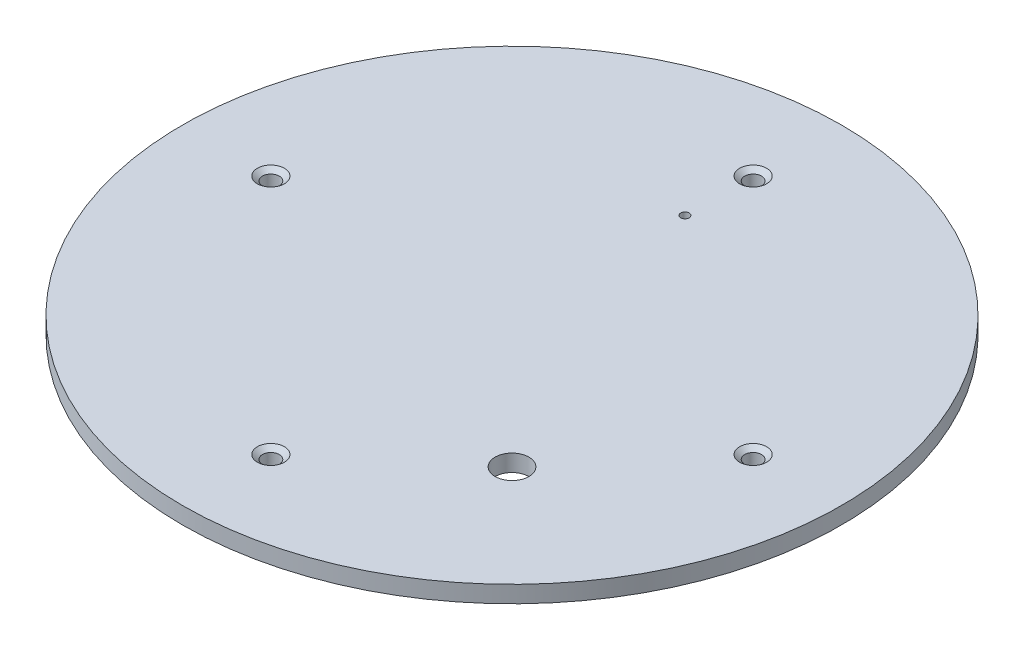
SolidWorks part; units mm, degrees
material "1060 Alloy"
ref_plane "Front Plane" through (0, 0, 0) normal (0, 0, 1) x (1, 0, 0)
ref_plane "Top Plane" through (0, 0, 0) normal (0, 1, 0) x (1, 0, 0)
ref_plane "Right Plane" through (0, 0, 0) normal (1, 0, 0) x (0, 0, -1)
sketch "Sketch1" plane through (0, 0, 0) normal (0, 1, 0) x (1, 0, 0)
  circle A0 centre (0, 0) radius 19.53
  dimension "D1" = 39.06
extrude "Boss-Extrude1" add sketch "Sketch1" along normal blind 1
sketch "Sketch6" plane through (0, 1, 0) normal (0, 1, 0) x (1, 0, 0)
  line L0 (0, 0) -> (14.1535, -14.1535) construction
  line L1 (0, 0) -> (17.9741, 0) construction
  circle A0 centre (0, 10.25) radius 0.25
  circle A1 centre (7.7782, -7.7782) radius 1
  dimension "D1" = 10.25
  dimension "D3" = 0.5
  dimension "D4" = 2
  dimension "D2" = 0
  dimension "D5" = 11
  dimension "D6" = 45
extrude "Cut-Extrude1" cut sketch "Sketch6" against normal through all both and the other way through all
hole_wizard "CSK for M2 Flat Head Machine Screw1" positions "Sketch7" profile "Sketch8" countersink size "M2" standard "ANSI Metric" end condition through all
sketch "Sketch7" plane through (0, 1, 0) normal (0, 1, 0) x (1, 0, 0)
  point P0 (0, 14.29)
  point P2 (-14.29, 0)
  point P4 (0, -14.29)
  point P6 (14.29, 0)
  dimension "D1" = 14.29
  dimension "D2" = 14.29
  dimension "D3" = 14.29
  dimension "D4" = 14.29
sketch "Sketch8" plane through (0, 1, -14.29) normal (1, 0, 0) x (0, 0, 1)
  line L0 (0, 0) -> (0, 1)
  line L1 (0, 1) -> (0.5, 1)
  line L2 (0.5, 1) -> (0.5, 0.2517)
  line L3 (0.5, 0.2517) -> (0.8, 0)
  line L5 (0.8, 0) -> (0, 0)
  line L6 (-0.5, 0.2517) -> (-0.8, 0) construction
  line L11 (0, -6.35) -> (0, 107.95) construction
  dimension "Thru Hole Dia." = 1
  dimension "Thru Hole Depth" = 1
  dimension "Near C'Sink Dia." = 1.6
  dimension "Near C'Sink Angle" = 100
